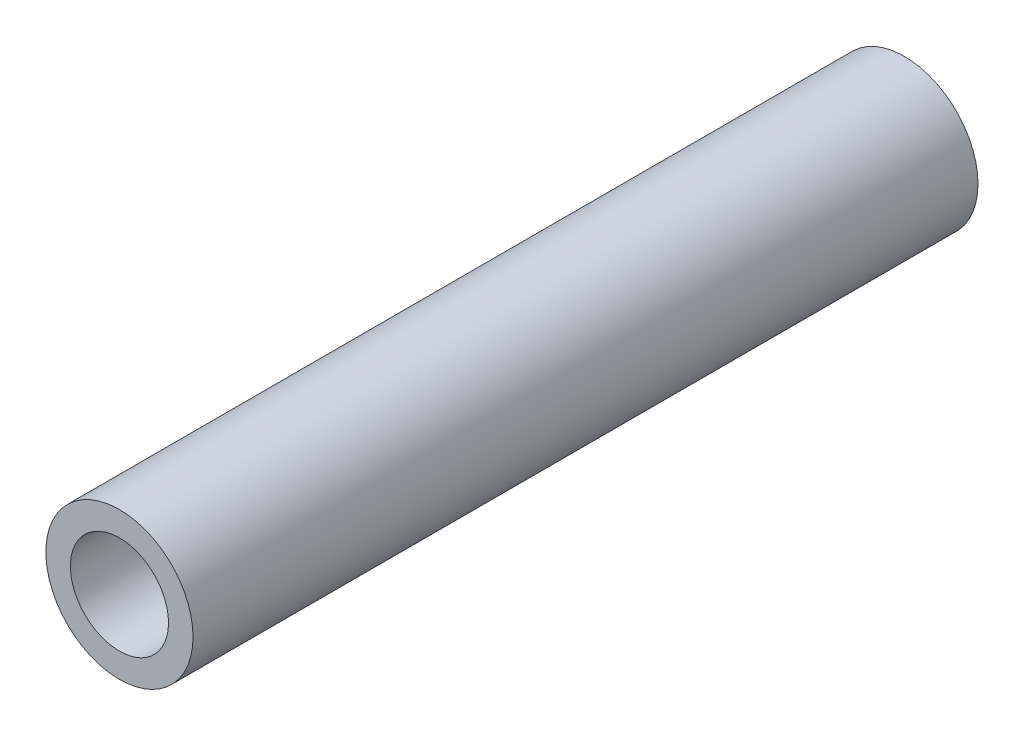
SolidWorks part; units mm, degrees
ref_plane "Front Plane" through (0, 0, 0) normal (0, 0, 1) x (1, 0, 0)
ref_plane "Top Plane" through (0, 0, 0) normal (0, 1, 0) x (1, 0, 0)
ref_plane "Right Plane" through (0, 0, 0) normal (1, 0, 0) x (0, 0, -1)
sketch "Sketch1" plane through (0, 0, 0) normal (0, 0, 1) x (1, 0, 0)
  circle A0 centre (0, 0) radius 3
  circle A1 centre (0, 0) radius 2
  dimension "D1" = 6
  dimension "D2" = 4
extrude "Boss-Extrude1" add sketch "Sketch1" along normal blind 32
